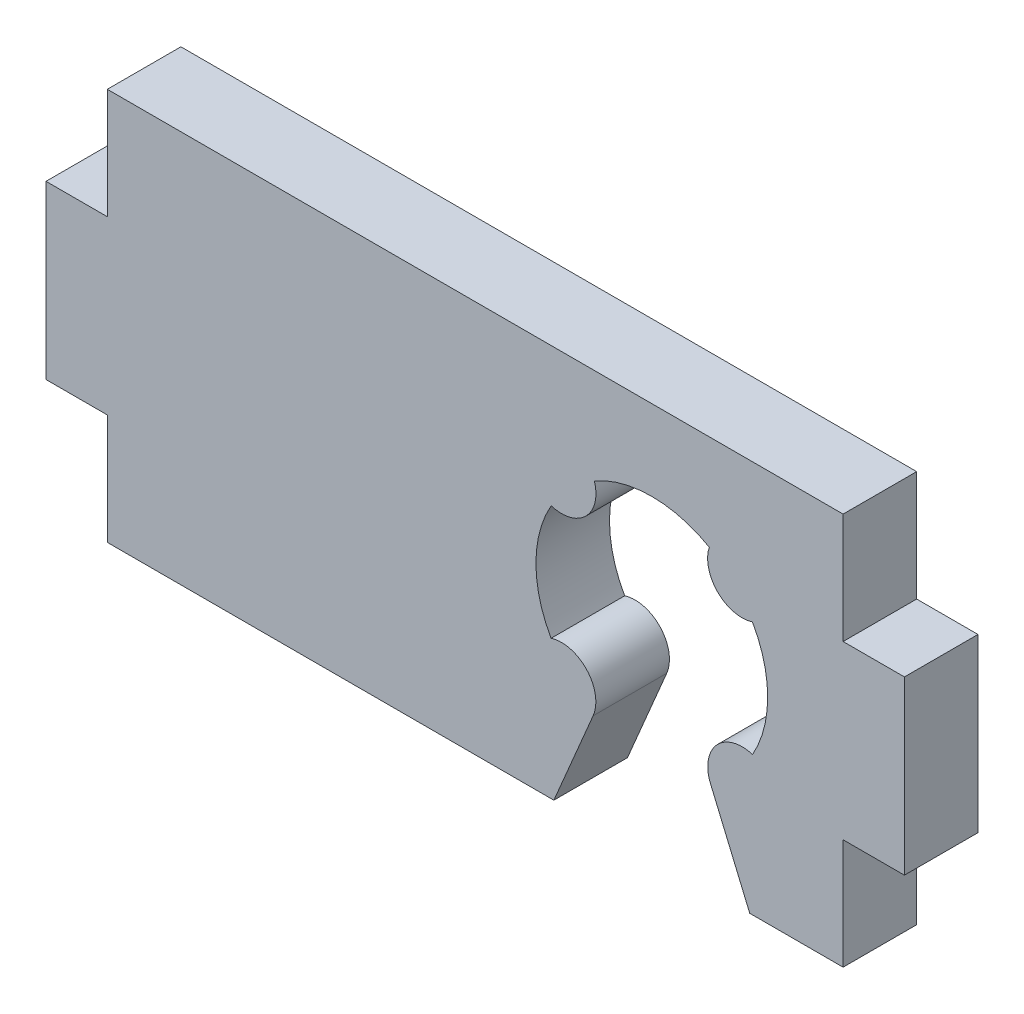
SolidWorks part; units mm, degrees
ref_plane "Plan de face" through (0, 0, 0) normal (0, 0, 1) x (1, 0, 0)
ref_plane "Plan de dessus" through (0, 0, 0) normal (0, 1, 0) x (1, 0, 0)
ref_plane "Plan de droite" through (0, 0, 0) normal (1, 0, 0) x (0, 0, -1)
sketch "Esquisse1" plane through (0, 0, 0) normal (0, 0, 1) x (1, 0, 0)
  line L0 (-24.7, -3.5) -> (-22.2, -3.5)
  line L1 (-24.7, -3.5) -> (-24.7, 3.5)
  line L2 (-24.7, 3.5) -> (-22.2, 3.5)
  line L4 (10.3, 3.5) -> (7.8, 3.5)
  line L5 (10.3, 3.5) -> (10.3, -3.5)
  line L6 (10.3, -3.5) -> (7.8, -3.5)
  line L7 (2.3922, -4.2184) -> (3.9934, -8)
  line L8 (-3.9934, -8) -> (-2.3922, -4.2184)
  line L9 (-22.2, 8) -> (-22.2, 3.5)
  line L10 (-22.2, -3.5) -> (-22.2, -8)
  line L11 (7.8, 3.5) -> (7.8, 8)
  line L12 (7.8, -8) -> (7.8, -3.5)
  line L13 (7.8, 8) -> (-22.2, 8)
  line L14 (-22.2, -8) -> (-3.9934, -8)
  line L16 (3.9934, -8) -> (7.8, -8)
  arc A0 (-4.103, 2.3433) -> (-4.1058, -2.3384) centre (0, 0) ccw
  arc A1 (2.3433, 4.103) -> (4.103, 2.3433) centre (3.677, 3.677) ccw
  arc A2 (4.1058, -2.3384) -> (2.3922, -4.2184) centre (3.6814, -3.6725) ccw
  arc A3 (-2.3922, -4.2184) -> (-4.1058, -2.3384) centre (-3.6814, -3.6725) ccw
  arc A4 (-4.103, 2.3433) -> (-2.3433, 4.103) centre (-3.677, 3.677) ccw
  arc A5 (2.3433, 4.103) -> (-2.3433, 4.103) centre (0, 0) ccw
  arc A6 (4.1058, -2.3384) -> (4.103, 2.3433) centre (0, 0) ccw
  circle A7 centre (0, 0) radius 5.2 construction
  dimension "D1" = 4.725
  dimension "D2" = 1.4
  dimension "D15" = 10.4
  dimension "D3" = 7
  dimension "D4" = 2.5
  dimension "D5" = 2.5
  dimension "D6" = 16
  dimension "D7" = 4.5
  dimension "D8" = 35
  dimension "D9" = 8
  dimension "D10" = 7.8
  dimension "D11" = 67.051
  dimension "D12" = 3.8066
  dimension "D13" = 112.949
  dimension "D14" = 18.2066
extrude "Boss.-Extru.1" add sketch "Esquisse1" along normal blind 3
